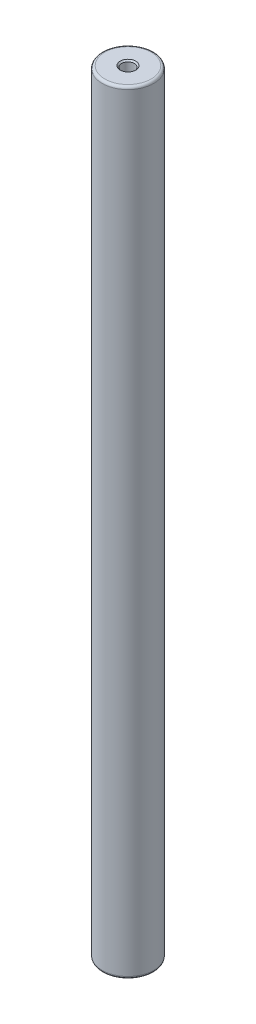
SolidWorks part; units mm, degrees
material "6061 合金"
ref_plane "前视基准面" through (0, 0, 0) normal (0, 0, 1) x (1, 0, 0)
ref_plane "上视基准面" through (0, 0, 0) normal (0, 1, 0) x (1, 0, 0)
ref_plane "右视基准面" through (0, 0, 0) normal (1, 0, 0) x (0, 0, -1)
sketch "草图1" plane through (0, 0, 0) normal (0, 1, 0) x (1, 0, 0)
  circle A0 centre (0, 0) radius 10
  dimension "D1" = 20
extrude "凸台-拉伸1" add sketch "草图1" along normal blind 300
hole_wizard "M6x1.0 螺纹孔2" positions "草图4" profile "草图5" tap size "M6x1.0" standard "ANSI Metric"
sketch "草图4" plane through (0, 300, 0) normal (0, 1, 0) x (1, 0, 0)
  point P0 (0, 0)
cosmetic thread "孔螺蚊线2" parameters "D1"=2.4, "D2"=6
sketch "草图5" plane through (0, 300, 0) normal (1, 0, 0) x (0, 0, 1)
  line L0 (0, 0) -> (0, 16.5022)
  line L1 (0, 16.5022) -> (2.5, 15)
  line L2 (2.5, 15) -> (2.5, 0.525)
  line L3 (2.5, 0.525) -> (3.025, 0)
  line L5 (3.025, 0) -> (0, 0)
  line L6 (-2.5, 0.525) -> (-3.025, 0) construction
  line L10 (0, 16.5022) -> (-2.5, 15) construction
  line L11 (0, -6.35) -> (0, 107.95) construction
  dimension "螺纹孔钻头直径" = 5
  dimension "螺纹孔钻头深度" = 15
  dimension "近端锥形沉头孔直径" = 6.05
  dimension "近端锥形沉头孔角度" = 90
  dimension "导头角度" = 118
fillet "圆角1" radius 1 1 edges at (0, 300, 10)
fillet "圆角2" radius 1 1 edges at (0, 0, 10)
